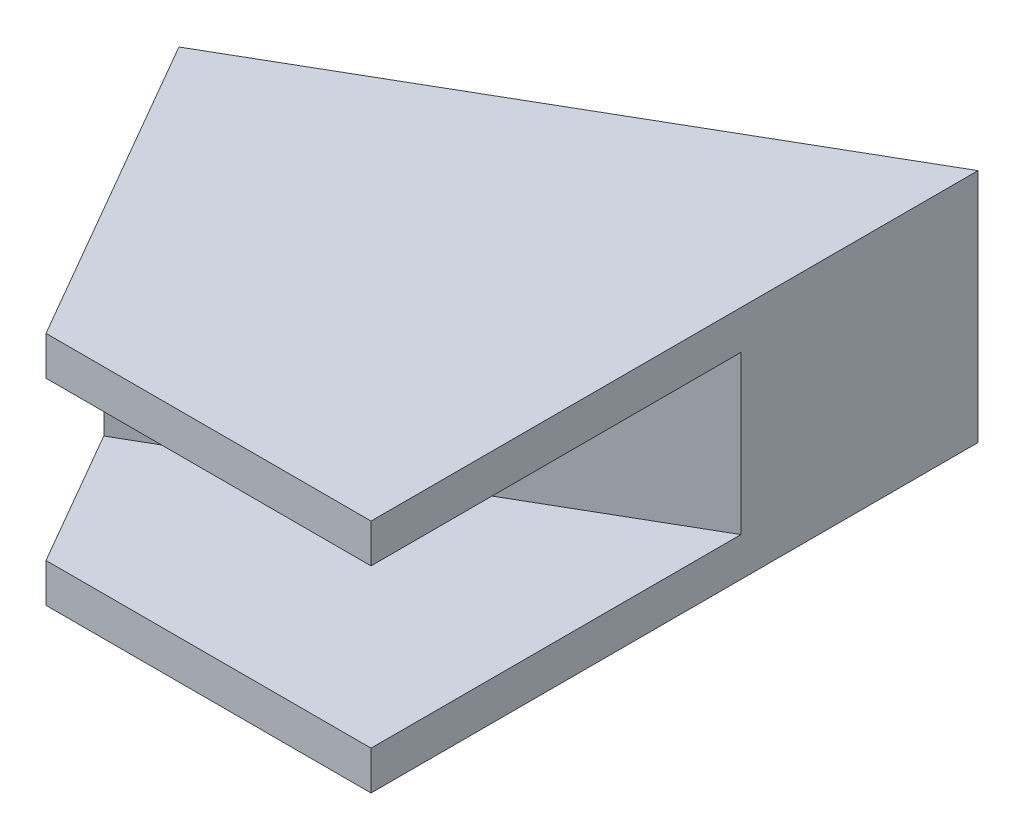
SolidWorks part; units mm, degrees
ref_plane "Front Plane" through (0, 0, 0) normal (0, 0, 1) x (1, 0, 0)
ref_plane "Top Plane" through (0, 0, 0) normal (0, 1, 0) x (1, 0, 0)
ref_plane "Right Plane" through (0, 0, 0) normal (1, 0, 0) x (0, 0, -1)
sketch "Sketch1" plane through (0, 0, 0) normal (0, 1, 0) x (1, 0, 0)
  line L0 (0, 0) -> (0, -24.1399) construction
  line L4 (0, 0) -> (-41.8115, -24.1399) construction
  line L5 (-41.8115, -24.1399) -> (0, -24.1399) construction
  line L6 (-41.8115, -24.1399) -> (-44.3115, -19.8098) construction
  line L7 (-44.3115, -19.8098) -> (0, 5.7735) construction
  line L8 (0, 5.7735) -> (0, 0) construction
  line L9 (-44.3115, -19.8098) -> (-51.9615, -6.5596) construction
  line L10 (0, 5.7735) -> (0, 23.4404) construction
  line L11 (-51.9615, -6.5596) -> (0, 23.4404) construction
  line L12 (-51.9615, -6.5596) -> (-54.4615, -2.2295) construction
  line L13 (-54.4615, -2.2295) -> (0, 29.2139) construction
  line L14 (0, 29.2139) -> (0, 23.4404) construction
  arc A0 (0, -3.7897) -> (-3.2819, -1.8948) centre (0, 0) cw construction
sketch "Sketch3" plane through (0, 0, 0) normal (0, 1, 0) x (1, 0, 0)
  line L0 (-54.4615, -2.2295) -> (-41.8115, -24.1399)
  line L1 (-41.8115, -24.1399) -> (0, -24.1399)
  line L2 (0, -24.1399) -> (0, 29.2139)
  line L3 (0, 29.2139) -> (-54.4615, -2.2295) construction
  line L4 (-54.4615, -2.2295) -> (-65.1668, 16.3126)
  line L5 (-65.1668, 16.3126) -> (0, 53.9367)
  line L6 (0, 53.9367) -> (0, 29.2139)
extrude "Boss-Extrude2" add sketch "Sketch3" along normal blind 5
sketch "Sketch4" plane through (0, 5, 0) normal (0, 1, 0) x (1, 0, 0)
  line L0 (-51.9615, -6.5596) -> (0, 23.4404)
  line L1 (-54.4615, -2.2295) -> (0, 29.2139) construction
  line L2 (-54.4615, -2.2295) -> (-51.9615, -6.5596)
  line L3 (0, 29.2139) -> (0, 23.4404)
  line L4 (-65.1668, 16.3126) -> (-54.4615, -2.2295)
  line L5 (-65.1668, 16.3126) -> (0, 53.9367)
  line L6 (0, 53.9367) -> (0, 29.2139)
extrude "Boss-Extrude3" add sketch "Sketch4" along normal blind 20.3
sketch "Sketch5" plane through (0, 25.3, 0) normal (0, 1, 0) x (1, 0, 0)
  line L0 (-65.1668, 16.3126) -> (-41.8115, -24.1399)
  line L1 (-41.8115, -24.1399) -> (0, -24.1399)
  line L2 (0, -24.1399) -> (0, 53.9367)
  line L3 (0, 53.9367) -> (-65.1668, 16.3126)
extrude "Boss-Extrude4" add sketch "Sketch5" along normal blind 5
